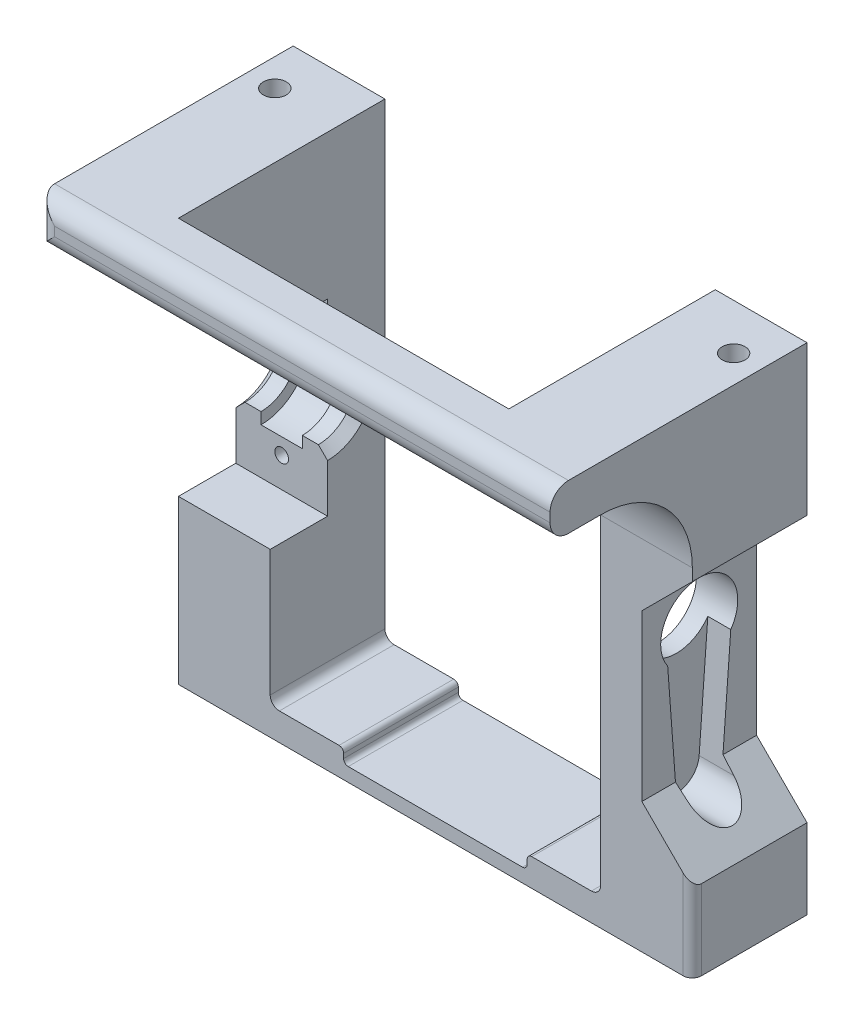
SolidWorks part; units mm, degrees
ref_plane "Спереди" through (0, 0, 0) normal (0, 0, 1) x (1, 0, 0)
ref_plane "Сверху" through (0, 0, 0) normal (0, 1, 0) x (1, 0, 0)
ref_plane "Справа" through (0, 0, 0) normal (1, 0, 0) x (0, 0, -1)
sketch "Эскиз1" plane through (0, 0, 0) normal (0, 0, 1) x (1, 0, 0)
  line L1 (-28, -27) -> (28, -27)
  line L2 (-28, -27) -> (-28, 27)
  line L3 (-28, 27) -> (28, 27)
  line L4 (28, -27) -> (28, 27)
  line L5 (-28, -27) -> (28, 27) construction
  line L6 (-28, 27) -> (28, -27) construction
  point P0 (0, 0)
  dimension "D1" = 56
  dimension "D2" = 54
extrude "тело" add sketch "Эскиз1" along normal blind 12.5
sketch "Эскиз3" plane through (0, 0, 12.5) normal (0, 0, 1) x (1, 0, 0)
  line L1 (-18, -24) -> (18, -24)
  line L2 (-18, -24) -> (-18, 22)
  line L3 (-18, 22) -> (18, 22)
  line L4 (18, -24) -> (18, 22)
  line L5 (-28, -27) -> (28, -27) construction
  point P0 (0, -1)
  point P6 (0, -24)
  point P9 (-18, -1)
  point P10 (0, -27)
  dimension "D1" = 36
  dimension "D2" = 46
  dimension "D3" = 3
extrude "отверстие под серво" cut sketch "Эскиз3" against normal through all
sketch "Эскиз11" plane through (0, -27, 0) normal (0, -1, 0) x (1, 0, 0)
  line L0 (0, 12.5) -> (0, 0) construction
  line L1 (-28, 12.5) -> (28, 12.5) construction
  line L2 (-25, 5) -> (25, 5) construction
  line L3 (-28, 0) -> (28, 0) construction
  circle A0 centre (-25, 5) radius 1.25
  circle A1 centre (25, 5) radius 1.25
  point P8 (0, 5)
  dimension "D1" = 2.5
  dimension "D2" = 50
  dimension "D3" = 5
extrude "Крепежные отверстия сверху" cut sketch "Эскиз11" against normal blind 10
mirror "Крепежные отверстия снизу" about plane through (0, 0, 0) normal (0, 1, 0) of "Крепежные отверстия сверху"
sketch "Эскиз5" plane through (28, 0, 0) normal (1, 0, 0) x (0, 0, -1)
  line L0 (-9.2, -1.2333) -> (-8.2445, -14.0487) construction
  line L1 (-6.25, 1) -> (-6.25, -15.9) construction
  line L2 (-6.25, 4.7) -> (-6.25, -15.9) construction
  line L3 (-9.2, -1.2333) -> (-6.25, -1.2333) construction
  line L4 (-6.25, -1.2333) -> (-6.25, -15.9) construction
  line L5 (-3.3, -1.2333) -> (-4.2555, -14.0487) construction
  line L6 (-9.688, -1.4125) -> (-8.7431, -14.0859)
  line L7 (-2.812, -1.4125) -> (-3.7569, -14.0859)
  line L8 (-12.5, -27) -> (0, -27) construction
  arc A0 (-2.812, -1.4125) -> (-9.688, -1.4125) centre (-6.25, 1) ccw
  arc A1 (-8.2445, -14.0487) -> (-4.2555, -14.0487) centre (-6.25, -13.9) ccw construction
  arc A2 (-8.7431, -14.0859) -> (-3.7569, -14.0859) centre (-6.25, -13.9) ccw
  arc A3 (-3.3, -1.2333) -> (-9.2, -1.2333) centre (-6.25, 1) ccw construction
  dimension "D1" = 2.95
  dimension "D2" = 4
  dimension "D4" = 7.4
  dimension "D5" = 0.5
  dimension "D3" = 20.6
  dimension "D6" = 28
extrude "вырез под качалку" cut sketch "Эскиз5" against normal offset from surface (8 mm away) 2 up to face at (18, -1, 6.25)
sketch "Эскиз4" plane through (28, 0, 0) normal (1, 0, 0) x (0, 0, -1)
  line L0 (-6.25, 27) -> (-6.25, -27) construction
  line L1 (-12.5, 27) -> (0, 27) construction
  line L2 (-12.5, -27) -> (0, -27) construction
  line L4 (-12.5, -27) -> (-12.5, 27) construction
  line L5 (-12.5, 0) -> (0, 0) construction
  line L6 (0, -27) -> (0, 27) construction
  circle A0 centre (-6.25, 1) radius 4.2
  arc A2 (-2.812, -1.4125) -> (-9.688, -1.4125) centre (-6.25, 1) ccw construction
extrude "вырез под ось вращения" cut sketch "Эскиз4" against normal up to next
sketch "Эскиз6" plane through (-28, 0, 0) normal (-1, 0, 0) x (0, 0, 1)
  circle A0 centre (6.25, 1) radius 4
  dimension "D1" = 8
extrude "вырез под ось подшипника" cut sketch "Эскиз6" against normal up to surface (10 mm away) up to face at (-18, -1, 6.25)
sketch "Эскиз7" plane through (-28, 0, 0) normal (-1, 0, 0) x (0, 0, 1)
  line L0 (12.5, 27) -> (12.5, -27) construction
  line L1 (6.25, 11.25) -> (12.5, 11.25)
  line L2 (6.25, 11.25) -> (6.25, -9.25)
  line L3 (6.25, -9.25) -> (12.5, -9.25)
  line L4 (12.5, 11.25) -> (12.5, -9.25)
  point P6 (6.25, 1)
  point P7 (6.25, 1)
  dimension "D1" = 20.5
extrude "вырез под крепление подшипника" cut sketch "Эскиз7" against normal up to surface (10 mm away) up to face at (-18, 1, 10.25)
ref_plane "Плоскость1" through (-23, 0, 0) normal (-1, 0, 0) x (0, 0, 1)
sketch "Эскиз8" plane through (-23, 0, 0) normal (-1, 0, 0) x (0, 0, 1)
  circle A0 centre (6.25, 1) radius 5.25
  dimension "D1" = 10.5
extrude "вырез под подшипник" cut sketch "Эскиз8" against normal mid plane 4.5
sketch "Эскиз9" plane through (0, 0, 6.25) normal (0, 0, 1) x (1, 0, 0)
  line L1 (-28, 1) -> (-18, 1) construction
  line L3 (-28, 5) -> (-28, -3) construction
  line L4 (-18, -3) -> (-18, 5) construction
  line L5 (-23, -6) -> (-23, 8) construction
  circle A0 centre (-23, 8) radius 0.75
  circle A1 centre (-23, -6) radius 0.75
  point P9 (-23, 1)
  dimension "D1" = 1.5
  dimension "D2" = 14
extrude "отверстия под саморезы" cut sketch "Эскиз9" against normal offset from surface (4.75 mm away) 1.5 up to face at (0, -1, 0)
sketch "Эскиз10" plane through (0, 0, 12.5) normal (0, 0, 1) x (1, 0, 0)
  line L1 (28, -27) -> (28, 27) construction
  line L2 (18, -24) -> (18, 22) construction
  line L3 (28, -18.3) -> (28, 10.7)
  line L4 (22.5, -12.8) -> (22.5, 5.2)
  line L5 (28, 10.7) -> (22.5, 5.2)
  line L6 (22.5, -12.8) -> (28, -18.3)
  line L8 (28, 5.2) -> (18, 5.2) construction
  dimension "D1" = 45
  dimension "D2" = 4.5
  dimension "D3" = 18
  dimension "D4" = 45
extrude "вырез чтобы вставлять качалку" cut sketch "Эскиз10" against normal through all
chamfer "Фаска1" distance 1 angle 45 2 edges at (-28, 1, 2.25) (-18, 1, 2.25)
fillet "Скругление1" radius 1 2 edges at (18, -24, 6.25) (-18, -24, 6.25)
sketch "Эскиз12" plane through (0, 0, 0) normal (0, 0, 1) x (1, 0, 0)
  line L0 (-17, -24) -> (17, -24) construction
  line L1 (-10, -24) -> (10, -24)
  line L2 (-10, -24) -> (-10, -25.5)
  line L3 (-10, -25.5) -> (10, -25.5)
  line L4 (10, -24) -> (10, -25.5)
  point P6 (0, -24)
  dimension "D1" = 20
  dimension "D2" = 1.5
extrude "вырез под шлейф" cut sketch "Эскиз12" along normal through all
fillet "Скругление2" radius 0.5 4 edges at (10, -25.5, 6.25) (10, -24, 6.25) (-10, -25.5, 6.25) (-10, -24, 6.25)
sketch "Эскиз13" plane through (0, 0, 12.5) normal (0, 0, 1) x (1, 0, 0)
  line L1 (-18, 22) -> (18, 22)
  line L2 (-18, 22) -> (-18, 27)
  line L3 (-18, 27) -> (18, 27)
  line L4 (18, 22) -> (18, 27)
  line L5 (28, 27) -> (-28, 27) construction
extrude "Удаление нижней перекладины" cut sketch "Эскиз13" against normal up to next
sketch "Эскиз14" plane through (0, 27, 0) normal (0, 1, 0) x (1, 0, 0)
  line L0 (-28, -12.5) -> (-28, -28)
  line L1 (0, 0) -> (0, -28) construction
  line L2 (-28, -12.5) -> (-18, -12.5)
  line L3 (-18, -12.5) -> (-18, -22.5)
  line L4 (-18, -22.5) -> (18, -22.5)
  line L5 (-28, -28) -> (28, -28)
  line L6 (18, -12.5) -> (18, -22.5)
  line L7 (28, -12.5) -> (18, -12.5)
  line L8 (28, -12.5) -> (28, -28)
  point P13 (0, -22.5)
  dimension "D1" = 15.5
  dimension "D2" = 10
extrude "Нижняя скоба жесткости" add sketch "Эскиз14" against normal blind 5
fillet "Скругление3" radius 10 2 edges at (23, 22, 12.5) (-23, 22, 12.5)
fillet "Скругление4" radius 2 4 edges at (0, 22, 28) (0, 27, 28) (-28, 24.5, 28) (0, 22, 22.5)
fillet "Скругление6" radius 1 1 edges at (28, -22.65, 12.5)
sketch "Эскиз15" plane through (0, 0, 0) normal (0, 0, -1) x (-1, 0, 0)
  line L0 (0, 27) -> (0, 0) construction
  line L1 (-18, 27) -> (18, 27) construction
  line L2 (-28, 27) -> (-18, 27) construction
  line L4 (-30.4, 13.1) -> (-28, 10.7)
  line L5 (-34, 27) -> (-28, 27)
  line L6 (-28, 10.7) -> (-28, 27) construction
  line L7 (-28, 10.7) -> (-22.5, 5.2) construction
  line L8 (-28, 10.7) -> (-28, 27)
  line L9 (-34, 20.05) -> (-28, 20.05) construction
  line L10 (-34, 13.1) -> (-30.4, 13.1)
  line L11 (34, 13.1) -> (28, 13.1)
  line L12 (34, 27) -> (28, 27)
  line L13 (28, 27) -> (28, -27) construction
  line L14 (28, 27) -> (28, 13.1)
  arc A0 (-36.5156, 15.2153) -> (-36.5156, 24.8847) centre (-34, 20.05) ccw
  arc A1 (-34, 27) -> (-37.208, 26.2153) centre (-34, 20.05) ccw
  arc A2 (-37.208, 26.2153) -> (-36.5156, 24.8847) centre (-36.8618, 25.55) ccw
  arc A4 (-37.208, 13.8847) -> (-36.5156, 15.2153) centre (-36.8618, 14.55) cw
  arc A5 (-37.208, 13.8847) -> (-34, 13.1) centre (-34, 20.05) ccw
  arc A6 (37.208, 13.8847) -> (34, 13.1) centre (34, 20.05) cw
  arc A7 (37.208, 13.8847) -> (36.5156, 15.2153) centre (36.8618, 14.55) ccw
  arc A8 (34, 27) -> (37.208, 26.2153) centre (34, 20.05) cw
  arc A9 (37.208, 26.2153) -> (36.5156, 24.8847) centre (36.8618, 25.55) cw
  arc A10 (36.5156, 15.2153) -> (36.5156, 24.8847) centre (34, 20.05) cw
  dimension "D1" = 10.9
  dimension "D2" = 1.5
  dimension "D3" = 34
  dimension "D4" = 11
extrude "Крепление фар" [suppressed] add sketch "Эскиз15" against normal blind 12.5
fillet "Скругление5" [suppressed] radius 1
